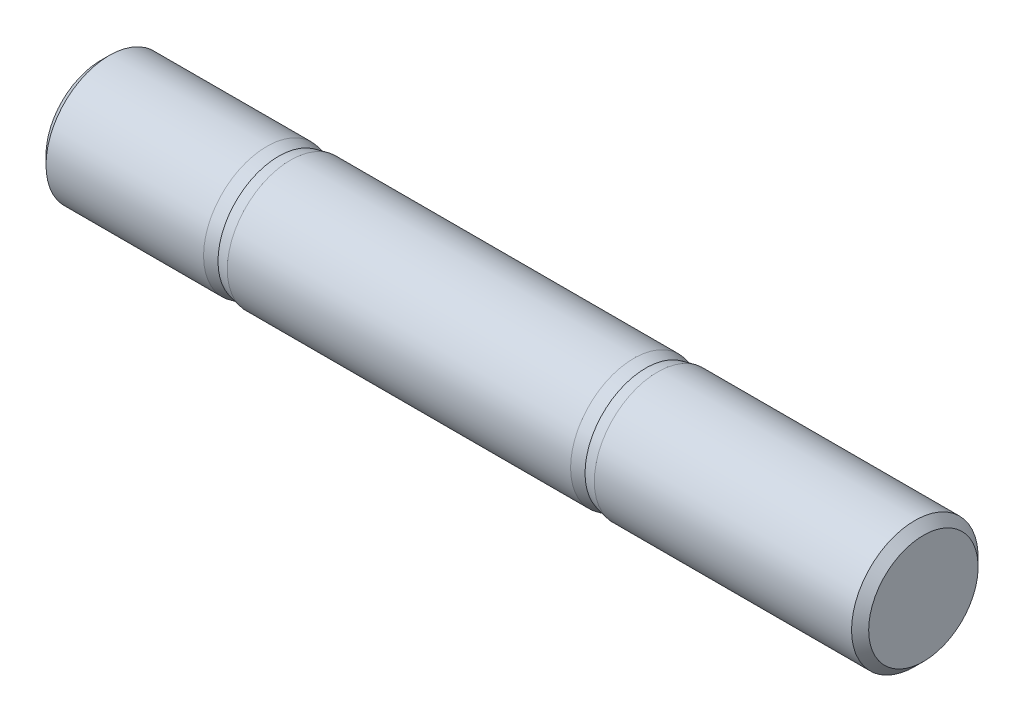
SolidWorks part; units mm, degrees
ref_plane "Front" through (0, 0, 0) normal (0, 0, 1) x (1, 0, 0)
ref_plane "Top" through (0, 0, 0) normal (0, 1, 0) x (1, 0, 0)
ref_plane "Right" through (0, 0, 0) normal (1, 0, 0) x (0, 0, -1)
sketch "Sketch1" plane through (0, 0, 0) normal (0, 0, 1) x (1, 0, 0)
  line L0 (-1.3108, 0) -> (30.3862, 0) construction
  line L1 (0, 0) -> (0, 10)
  line L2 (0, 10) -> (26.25, 10)
  line L3 (26.25, 10) -> (30, 9.188)
  line L4 (30, 9.188) -> (84.25, 9.188)
  line L5 (84.25, 9.188) -> (88, 10)
  line L6 (88, 10) -> (130, 10)
  line L7 (130, 10) -> (130, 0)
  line L8 (130, 0) -> (0, 0)
  dimension "X" = 3.75
  dimension "D2" = 3.75
  dimension "b" = 42
  dimension "d" = 20
  dimension "ds" = 18.376
  dimension "l" = 100
  dimension "bm" = 30
revolve "BaseHead" add sketch "Sketch1" angle 360 about L0
cosmetic thread "ThreadCosmetic1" [suppressed] parameters "D1"=26.25, "D2"=17.294
cosmetic thread "ThreadCosmetic2" [suppressed] parameters "b"=42, "D2"=17.294
chamfer "HeadChamfer" distance 1.353 angle 45 2 edges at (0, 0, 10) (130, 0, 10)
sketch "Sketch2" plane through (0, 0, 0) normal (0, 0, 1) x (1, 0, 0)
  line L0 (-1.3108, 0) -> (31.2107, 0) construction
  line L2 (26.25, 9.188) -> (30, 10)
  line L3 (30, 10) -> (84.25, 10)
  line L4 (84.25, 10) -> (88, 9.188)
  line L7 (26.25, 10) -> (26.25, -10) construction
  line L9 (26.25, 9.188) -> (88, 9.188)
  line L10 (88, 10) -> (88, -10) construction
  dimension "D2" = 20
  dimension "D1" = 3.75
revolve "BaseBody" add sketch "Sketch2" angle 360 about L0
sketch "Sketch3" plane through (0, 0, 0) normal (0, 0, 1) x (1, 0, 0)
  line L0 (128.647, 8.8283) -> (129.3235, 10)
  line L1 (129.3235, 10) -> (129.3235, 10.5)
  line L2 (129.3235, 10.5) -> (127.9705, 10.5)
  line L3 (127.9705, 10.5) -> (127.9705, 10)
  line L4 (127.9705, 10) -> (128.647, 8.8283)
  line L5 (0, 0) -> (54.5942, 0) construction
  line L6 (128.647, 10) -> (128.647, -10) construction
  dimension "D1" = 60
  dimension "D2" = 60
  dimension "D3" = 0.5
  dimension "D4" = 1.353
  dimension "D5" = 20
revolve "Cut-Revolve10" [suppressed] cut sketch "Sketch3" angle 360 about L5
pattern_linear "LPattern10" [suppressed] count 26 spacing 1.6236 along (1, 0, 0)
sketch "Sketch4" plane through (0, 0, 0) normal (0, 0, 1) x (1, 0, 0)
  line L0 (1.353, 8.8283) -> (2.0295, 10)
  line L1 (2.0295, 10) -> (2.0295, 10.5)
  line L2 (2.0295, 10.5) -> (0.6765, 10.5)
  line L3 (0.6765, 10.5) -> (0.6765, 10)
  line L4 (0.6765, 10) -> (1.353, 8.8283)
  line L5 (0, 0) -> (16.1581, 0) construction
  line L6 (0, 8.647) -> (0, -8.647) construction
  line L7 (1.353, 10) -> (1.353, -10) construction
  dimension "D1" = 60
  dimension "D2" = 60
  dimension "D3" = 0.5
  dimension "D4" = 1.353
  dimension "D5" = 20
revolve "Cut-Revolve11" [suppressed] cut sketch "Sketch4" angle 360 about L5
pattern_linear "LPattern11" [suppressed] count 16 spacing 1.6236 along (1, 0, 0)
equation "\"D2@Sketch1\" = \"X@Sketch1\""
equation "\"D2@ThreadCosmetic2\" = \"D2@ThreadCosmetic1\""
equation "\"D1@ThreadCosmetic1\" = \"bm@Sketch1\"-\"X@Sketch1\""
equation "\"b@ThreadCosmetic2\" = \"b@Sketch1\""
equation "\"D1@Sketch2\" = \"X@Sketch1\""
equation "\"D2@Sketch2\" = \"d@Sketch1\""
equation "\"D1@HeadChamfer\" =  ( \"d@Sketch1\" - \"D2@ThreadCosmetic1\" )  / 2"
equation "\"D5@Sketch3\" = \"d@Sketch1\""
equation "\"D4@Sketch3\" = (  \"d@Sketch1\" - \"D2@ThreadCosmetic2\" )  / 2"
equation "\"D3@LPattern10\" = \"D4@Sketch3\" * 1.2"
equation "\"D1@LPattern10\" = \"b@ThreadCosmetic2\" / \"D3@LPattern10\""
equation "\"D5@Sketch4\" = \"d@Sketch1\""
equation "\"D4@Sketch4\" = (  \"d@Sketch1\" - \"D2@ThreadCosmetic1\" )  / 2"
equation "\"D3@LPattern11\" = \"D4@Sketch4\" * 1.2"
equation "\"D1@LPattern11\" = \"D1@ThreadCosmetic1\" / \"D3@LPattern11\""
